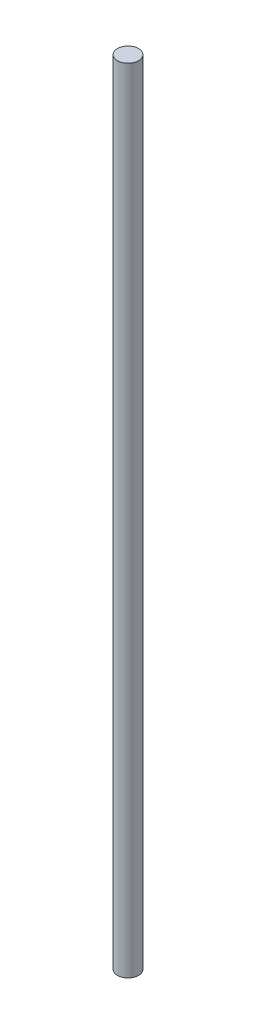
SolidWorks part; units mm, degrees
ref_plane "Front Plane" through (0, 0, 0) normal (0, 0, 1) x (1, 0, 0)
ref_plane "Top Plane" through (0, 0, 0) normal (0, 1, 0) x (1, 0, 0)
ref_plane "Right Plane" through (0, 0, 0) normal (1, 0, 0) x (0, 0, -1)
sketch "Sketch1" plane through (0, 0, 0) normal (0, 0, 1) x (1, 0, 0)
  line L0 (0, 308.5599) -> (5.08, 308.5599)
  line L1 (5.08, 308.5599) -> (5.08, -72.4401)
  line L2 (5.08, -72.4401) -> (0, -72.4401)
  line L3 (0, -72.4401) -> (0, 308.5599)
  dimension "D1" = 381
  dimension "D2" = 5.08
revolve "Revolve1" add sketch "Sketch1" angle 360 about L3
